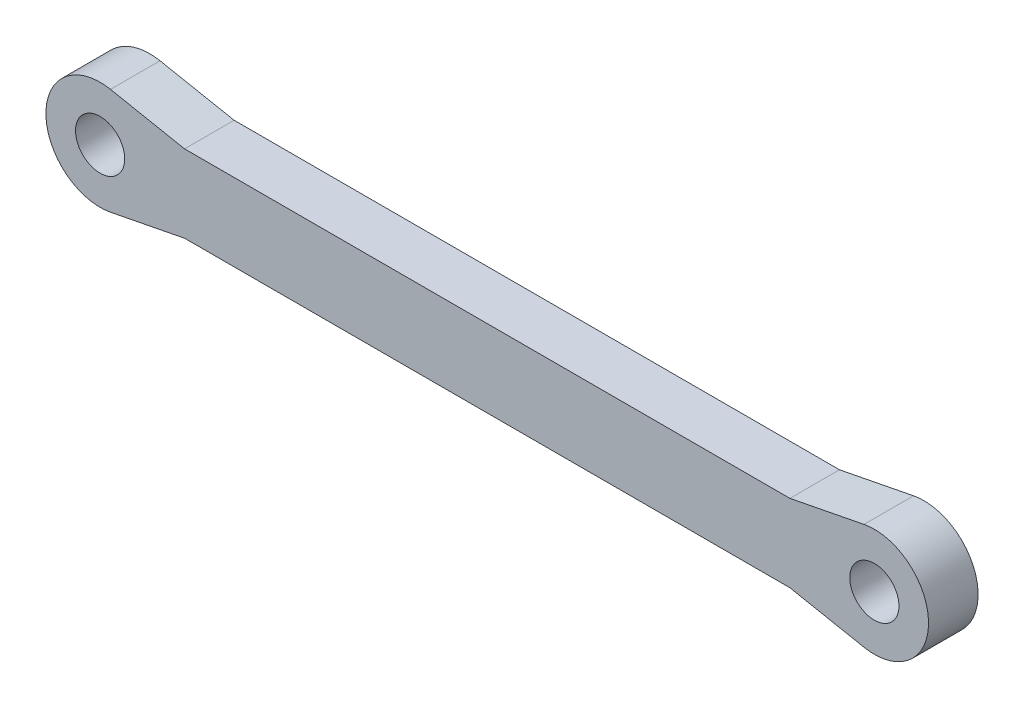
SolidWorks part; units mm, degrees
ref_plane "Front Plane" through (0, 0, 0) normal (0, 0, 1) x (1, 0, 0)
ref_plane "Top Plane" through (0, 0, 0) normal (0, 1, 0) x (1, 0, 0)
ref_plane "Right Plane" through (0, 0, 0) normal (1, 0, 0) x (0, 0, -1)
sketch "Sketch1" plane through (0, 0, 0) normal (0, 0, 1) x (1, 0, 0)
  line L0 (19.5456, -2.5) -> (-19.5456, -2.5)
  line L1 (-19.5456, -2.5) -> (-24.3285, -3.435)
  line L2 (19.5456, 2.5) -> (-19.5456, 2.5)
  line L3 (-19.5456, 2.5) -> (-24.3285, 3.435)
  line L4 (19.5456, -2.5) -> (24.3285, -3.435)
  line L5 (19.5456, 2.5) -> (24.3285, 3.435)
  line L6 (0, 2.5) -> (0, -2.5) construction
  circle A0 centre (-25, 0) radius 1.5875
  arc A2 (-24.3285, 3.435) -> (-24.3285, -3.435) centre (-25, 0) ccw
  circle A3 centre (25, 0) radius 1.5875
  arc A5 (24.3285, -3.435) -> (24.3285, 3.435) centre (25, 0) ccw
extrude "Boss-Extrude1" add sketch "Sketch1" along normal mid plane 3.2
